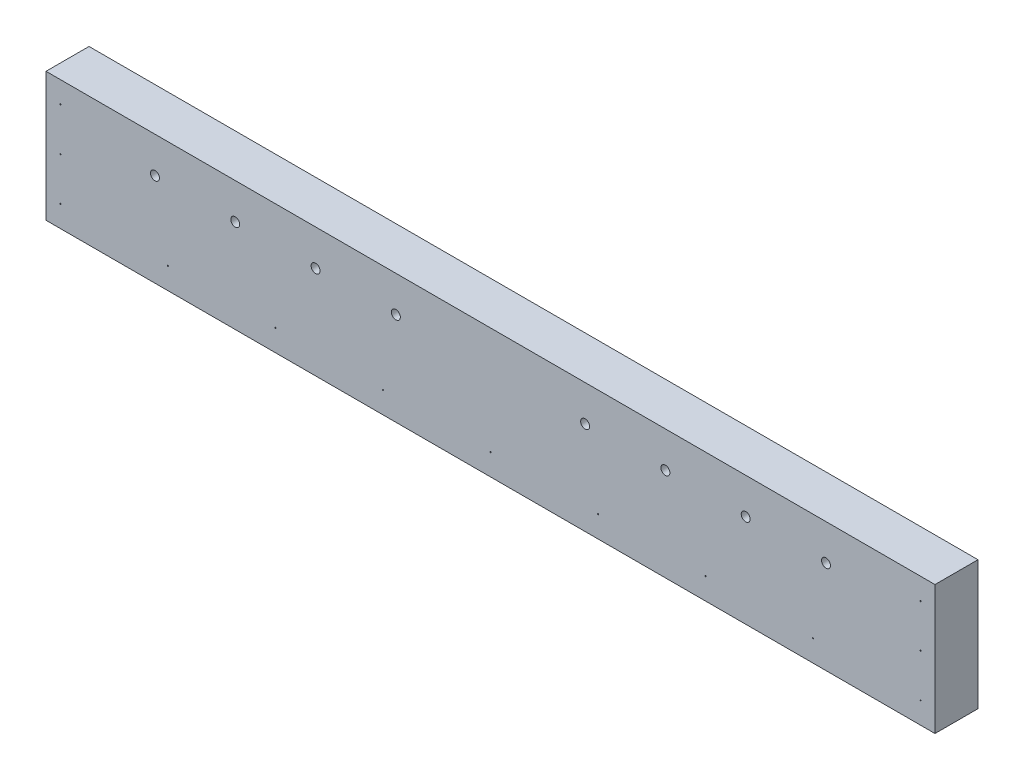
SolidWorks part; units mm, degrees
ref_plane "Front Plane" through (0, 0, 0) normal (0, 0, 1) x (1, 0, 0)
ref_plane "Top Plane" through (0, 0, 0) normal (0, 1, 0) x (1, 0, 0)
ref_plane "Right Plane" through (0, 0, 0) normal (1, 0, 0) x (0, 0, -1)
sketch "Sketch1" plane through (0, 0, 0) normal (0, 0, 1) x (1, 0, 0)
  line L1 (0, 0) -> (1574.8, 0)
  line L2 (0, 0) -> (0, 228.6)
  line L3 (0, 228.6) -> (1574.8, 228.6)
  line L4 (1574.8, 0) -> (1574.8, 228.6)
  dimension "D1" = 1574.8
  dimension "D2" = 228.6
extrude "Boss-Extrude1" add sketch "Sketch1" along normal blind 76.2
sketch "Sketch2" plane through (0, 0, 76.2) normal (0, 0, 1) x (1, 0, 0)
  line L0 (0, 165.1) -> (1574.8, 165.1) construction
  line L1 (0, 228.6) -> (0, 0) construction
  line L2 (1574.8, 0) -> (1574.8, 228.6) construction
  line L3 (0, 0) -> (1574.8, 0) construction
  circle A0 centre (193.04, 165.1) radius 7.9375
  circle A1 centre (335.28, 165.1) radius 7.9375
  circle A2 centre (477.52, 165.1) radius 7.9375
  circle A3 centre (619.76, 165.1) radius 7.9375
  circle A5 centre (955.04, 165.1) radius 7.9375
  circle A6 centre (1097.28, 165.1) radius 7.9375
  circle A7 centre (1239.52, 165.1) radius 7.9375
  circle A8 centre (1381.76, 165.1) radius 7.9375
  dimension "D1" = 15.875
  dimension "D2" = 15.875
  dimension "D3" = 15.875
  dimension "D4" = 15.875
  dimension "D6" = 15.875
  dimension "D7" = 15.875
  dimension "D8" = 15.875
  dimension "D9" = 15.875
  dimension "D12" = 477.52
  dimension "D13" = 619.76
  dimension "D10" = 193.04
  dimension "D11" = 335.28
  dimension "D14" = 193.04
  dimension "D15" = 335.28
  dimension "D16" = 477.52
  dimension "D17" = 619.76
  dimension "D18" = 165.1
extrude "Cut-Extrude1" cut sketch "Sketch2" against normal through all
sketch "Sketch3" plane through (0, 0, 76.2) normal (0, 0, 1) x (1, 0, 0)
  line L0 (1574.8, 0) -> (1574.8, 228.6) construction
  line L1 (0, 0) -> (1574.8, 0) construction
  line L2 (1574.8, 228.6) -> (0, 228.6) construction
  line L3 (787.4, 0) -> (787.4, 228.6) construction
  circle A0 centre (1549.4, 38.1) radius 0.9922
  circle A1 centre (1549.4, 190.5) radius 1.016
  circle A2 centre (1549.4, 114.3) radius 1.016
  circle A3 centre (25.4, 38.1) radius 0.9922
  circle A4 centre (25.4, 114.3) radius 1.016
  circle A5 centre (25.4, 190.5) radius 1.016
  circle A6 centre (215.9, 38.1) radius 1.016
  circle A7 centre (406.4, 38.1) radius 1.016
  circle A8 centre (596.9, 38.1) radius 1.016
  circle A9 centre (787.4, 38.1) radius 1.016
  circle A10 centre (977.9, 38.1) radius 1.016
  circle A11 centre (1168.4, 38.1) radius 1.016
  circle A12 centre (1358.9, 38.1) radius 1.016
  point P12 (1574.8, 114.3)
  dimension "D1" = 1.9844
  dimension "D6" = 2.032
  dimension "D8" = 2.032
  dimension "D13" = 2.032
  dimension "D14" = 2.032
  dimension "D15" = 2.032
  dimension "D16" = 2.032
  dimension "D2" = 25.4
  dimension "D3" = 38.1
  dimension "D4" = 38.1
  dimension "D5" = 25.4
  dimension "D7" = 25.4
  dimension "D9" = 0
  dimension "D10" = 190.5
  dimension "D11" = 190.5
  dimension "D12" = 190.5
extrude "Cut-Extrude2" cut sketch "Sketch3" against normal blind 76.2
